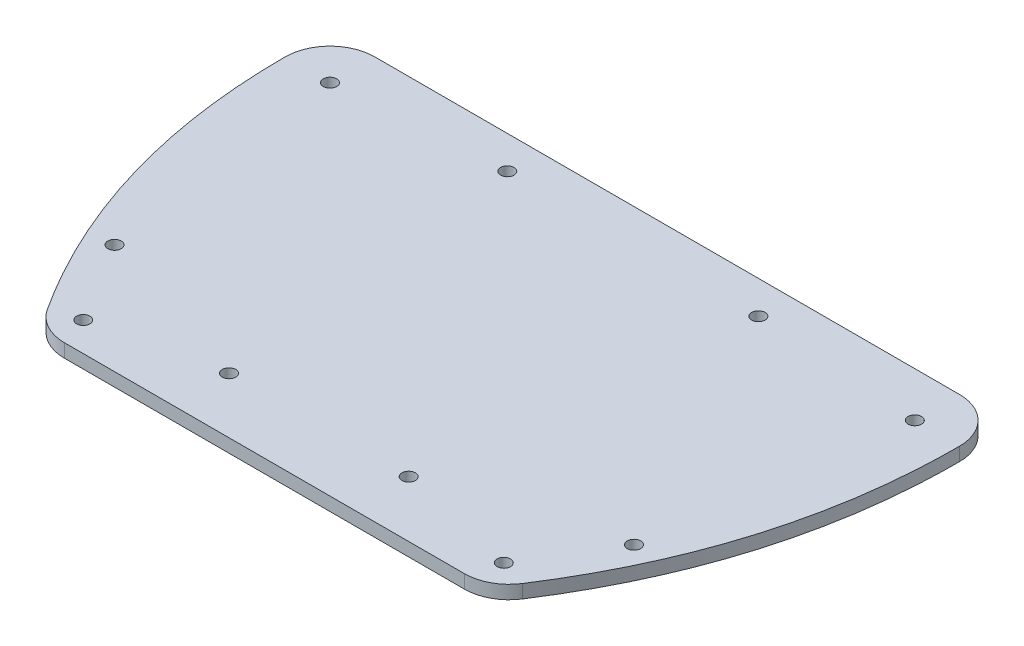
SolidWorks part; units mm, degrees
ref_plane "前视基准面" through (0, 0, 0) normal (0, 0, 1) x (1, 0, 0)
ref_plane "上视基准面" through (0, 0, 0) normal (0, 1, 0) x (1, 0, 0)
ref_plane "右视基准面" through (0, 0, 0) normal (1, 0, 0) x (0, 0, -1)
sketch "草图1" plane through (0, 0, 0) normal (0, 1, 0) x (1, 0, 0)
  line L0 (0, 78.6735) -> (0, -87.8571) construction
  line L1 (-65.342, 0) -> (65.342, 0)
  line L2 (-44.6767, -90) -> (44.6767, -90)
  arc A0 (-44.6767, -90) -> (-53.073, -85.4317) centre (-44.6767, -80) cw
  arc A1 (44.6767, -90) -> (53.073, -85.4317) centre (44.6767, -80) ccw
  arc A2 (75.342, -9.9848) -> (65.342, 0) centre (65.342, -10) ccw
  arc A3 (-65.342, 0) -> (-75.342, -9.9848) centre (-65.342, -10) ccw
  spline S0 degree 3 poles (-75.342, -9.9848) (-75.3626, -23.5867) (-71.6571, -49.8946) (-60.5388, -73.8909) (-53.073, -85.4317) knots 0.101766 0.101766 0.101766 0.101766 0.521593 0.943927 0.943927 0.943927 0.943927
  spline S1 degree 3 poles (75.342, -9.9848) (75.3626, -23.5867) (71.6571, -49.8946) (60.5388, -73.8909) (53.073, -85.4317) knots 0.101766 0.101766 0.101766 0.101766 0.521593 0.943927 0.943927 0.943927 0.943927
  point P6 (0, 0)
  point P9 (0, -90)
  dimension "D3" = 10
  dimension "D2" = 90
extrude "凸台-拉伸1" add sketch "草图1" along normal blind 3
sketch "草图2" plane through (0, 3, 0) normal (0, 1, 0) x (1, 0, 0)
  line L0 (0, 0) -> (0, -107.4204) construction
  circle A0 centre (-65.342, -10) radius 1.5
  circle A1 centre (-46.9865, -83.4972) radius 1.5
  circle A2 centre (46.9865, -83.4972) radius 1.5
  circle A3 centre (65.342, -10) radius 1.5
  dimension "D1" = 3
  dimension "D2" = 3
extrude "切除-拉伸1" cut sketch "草图2" against normal blind 10
sketch "草图3" plane through (0, 3, 0) normal (0, 1, 0) x (1, 0, 0)
  circle A0 centre (-28.3878, -7.3403) radius 1.5
  circle A1 centre (27.7186, -7.3403) radius 1.5
  circle A2 centre (19.6955, -77.462) radius 1.5
  circle A3 centre (-20.3846, -77.522) radius 1.5
  dimension "D1" = 3
  dimension "D2" = 3
  dimension "D3" = 3
  dimension "D4" = 3
extrude "切除-拉伸2" cut sketch "草图3" against normal blind 10
sketch "草图4" plane through (0, 3, 0) normal (0, 1, 0) x (1, 0, 0)
  line L0 (0, -30.5907) -> (0, -43.2549) construction
  circle A0 centre (-58.0337, -65.4582) radius 1.5
  circle A1 centre (58.0337, -65.4582) radius 1.5
  dimension "D1" = 3
extrude "切除-拉伸3" cut sketch "草图4" against normal blind 3
